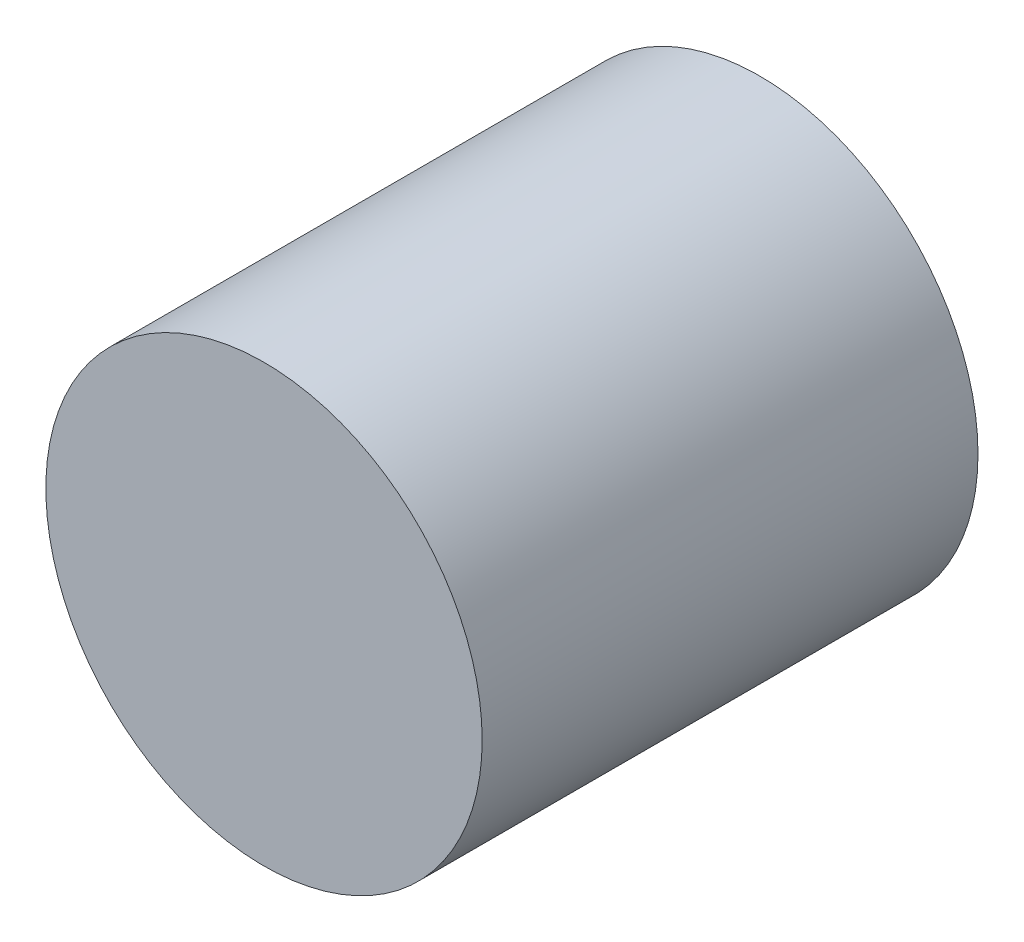
SolidWorks part; units mm, degrees
ref_plane "Front Plane" through (0, 0, 0) normal (0, 0, 1) x (1, 0, 0)
ref_plane "Top Plane" through (0, 0, 0) normal (0, 1, 0) x (1, 0, 0)
ref_plane "Right Plane" through (0, 0, 0) normal (1, 0, 0) x (0, 0, -1)
sketch "Sketch1" plane through (0, 0, 0) normal (0, 0, 1) x (1, 0, 0)
  circle A0 centre (0, 0) radius 27.94
  point P3 (0, 0)
  point P4 (0, 0)
extrude "Boss-Extrude1" add sketch "Sketch1" along normal blind 63.5
